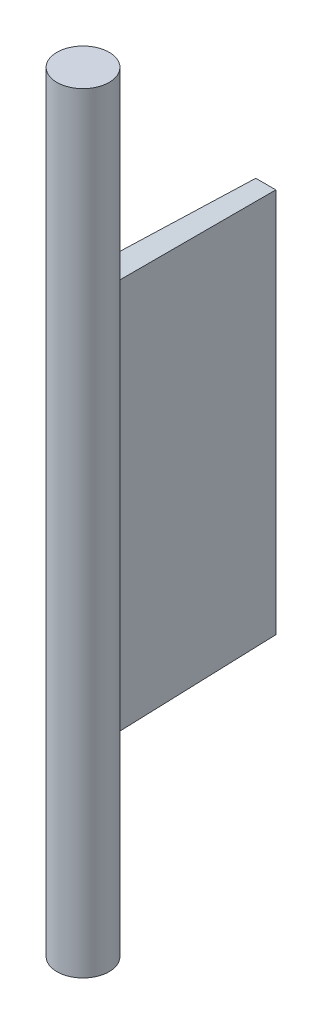
SolidWorks part; units mm, degrees
ref_plane "Ebene vorne" through (0, 0, 0) normal (0, 0, 1) x (1, 0, 0)
ref_plane "Ebene oben" through (0, 0, 0) normal (0, 1, 0) x (1, 0, 0)
ref_plane "Ebene rechts" through (0, 0, 0) normal (1, 0, 0) x (0, 0, -1)
sketch "Skizze2" plane through (0, 0, 0) normal (0, 1, 0) x (1, 0, 0)
  circle A0 centre (0, 0) radius 10
  dimension "D1" = 20
extrude "Aufsatz-Linear austragen1" add sketch "Skizze2" along normal blind 295
sketch "Skizze7" plane through (0, 0, 0) normal (0, 0, 1) x (1, 0, 0)
  line L0 (-10, 0) -> (10, 0) construction
  line L1 (5.067, 222.5) -> (-5.067, 222.5)
  line L2 (5.067, 222.5) -> (5.067, 72.5)
  line L3 (5.067, 72.5) -> (-5.067, 72.5)
  line L4 (-5.067, 222.5) -> (-5.067, 72.5)
  line L5 (5.067, 222.5) -> (-5.067, 72.5) construction
  line L6 (5.067, 72.5) -> (-5.067, 222.5) construction
  point P0 (0, 147.5)
  dimension "D1" = 150
  dimension "D2" = 72.5
extrude "Aufsatz-Linear austragen2" add sketch "Skizze7" against normal blind 70 draft 1
